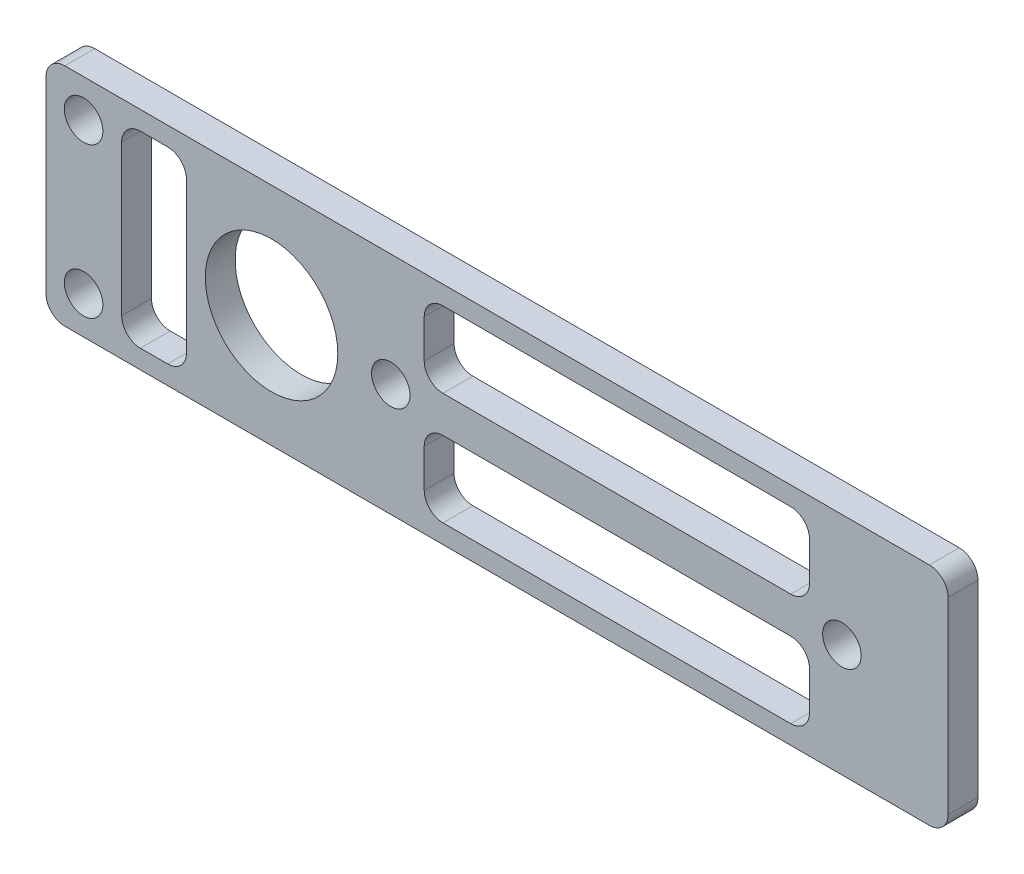
SolidWorks part; units mm, degrees
ref_plane "Front Plane" through (0, 0, 0) normal (0, 0, 1) x (1, 0, 0)
ref_plane "Top Plane" through (0, 0, 0) normal (0, 1, 0) x (1, 0, 0)
ref_plane "Right Plane" through (0, 0, 0) normal (1, 0, 0) x (0, 0, -1)
sketch "Sketch1" plane through (0, 0, 0) normal (0, 0, 1) x (1, 0, 0)
  line L0 (0, 0) -> (50000, 0) construction
  line L1 (48, -12) -> (-48, -12)
  line L2 (48, -12) -> (48, 12)
  line L3 (48, 12) -> (-48, 12)
  line L4 (-48, -12) -> (-48, 12)
  line L5 (48, -12) -> (-48, 12) construction
  line L6 (48, 12) -> (-48, -12) construction
  line L7 (50, 14) -> (-50, 14) construction
  line L8 (-50, -14) -> (-50, 14) construction
  line L9 (50, -14) -> (-50, -14) construction
  line L10 (50, -14) -> (50, 14) construction
  line L11 (0, -2) -> (50000, -2) construction
  line L12 (46, 10) -> (-46, 10) construction
  line L13 (-46, -10) -> (-46, 10) construction
  line L14 (46, -10) -> (-46, -10) construction
  line L15 (46, -10) -> (46, 10) construction
  line L16 (0, 2) -> (50000, 2) construction
  line L17 (-7.7541, -10) -> (33.2459, -10)
  line L18 (-7.7541, 1.9385) -> (33.2459, 1.9385)
  line L19 (-7.7541, 1.9385) -> (-7.7541, 10)
  line L20 (-7.7541, 10) -> (33.2459, 10)
  line L21 (33.2459, 1.9385) -> (33.2459, 10)
  line L22 (33.2459, -1.9385) -> (33.2459, -10)
  line L23 (-7.7541, -1.9385) -> (33.2459, -1.9385)
  line L24 (-7.7541, -1.9385) -> (-7.7541, -10)
  line L26 (-39.95, 10) -> (-33.05, 10)
  line L27 (-39.95, 10) -> (-39.95, -10)
  line L28 (-39.95, -10) -> (-33.05, -10)
  line L29 (-33.05, 10) -> (-33.05, -10)
  circle A0 centre (-24, 0) radius 7.05
  circle A1 centre (-11.31, 0) radius 2.05
  circle A2 centre (36.69, 0) radius 2.05
  circle A3 centre (-24, 0) radius 9.05 construction
  circle A4 centre (-11.31, 0) radius 4.05 construction
  circle A5 centre (36.69, 0) radius 4.05 construction
  circle A6 centre (-44, 8) radius 2.05
  circle A7 centre (-44, -8) radius 2.05
  circle A8 centre (-44, 8) radius 4.05 construction
  circle A9 centre (-44, 8) radius 0.05 construction
  circle A10 centre (-44, -8) radius 4.05 construction
  circle A11 centre (-44, -8) radius 0.05 construction
  point P0 (0, 0)
  point P25 (-7.26, 0)
  point P26 (-33.05, 0)
  dimension "D3" = 14.1
  dimension "D6" = 4.1
  dimension "D12" = 4.1
  dimension "D1" = 96
  dimension "D2" = 24
  dimension "D4" = 24
  dimension "D5" = 48
  dimension "D7" = 36.69
  dimension "D11" = 41
  dimension "D13" = 4
  dimension "D14" = 4
  dimension "D8" = 2
  dimension "D9" = 2
  dimension "D10" = 2
  dimension "D15" = 2
  dimension "D16" = 2
  dimension "D17" = 2
  dimension "D18" = 2
extrude "Boss-Extrude1" add sketch "Sketch1" along normal blind 3.175
fillet "Fillet1" radius 2 16 edges at (-39.95, -10, 1.5875) (-39.95, 10, 1.5875) (-33.05, 10, 1.5875) (-33.05, -10, 1.5875) (33.2459, 1.9385, 1.5875) (33.2459, 10, 1.5875) (-7.7541, -1.9385, 1.5875) (33.2459, -10, 1.5875) (33.2459, -1.9385, 1.5875) (-7.7541, -10, 1.5875) (-7.7541, 1.9385, 1.5875) (-7.7541, 10, 1.5875) (48, 12, 1.5875) (48, -12, 1.5875) (-48, -12, 1.5875) (-48, 12, 1.5875)
